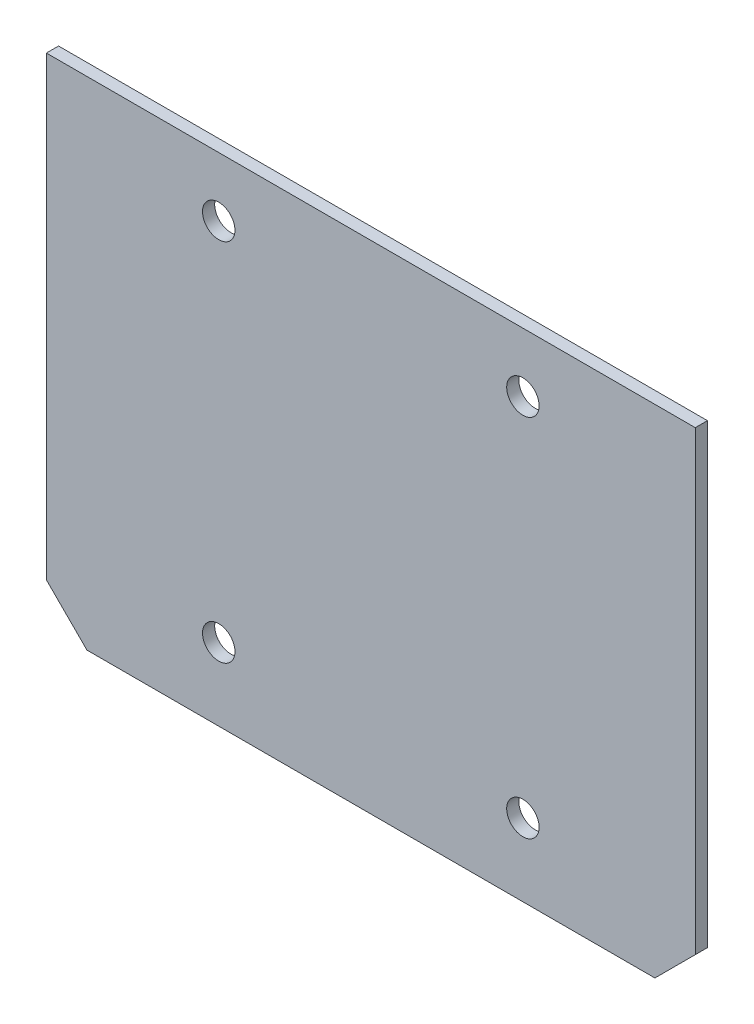
SolidWorks part; units mm, degrees
ref_plane "Front Plane" through (0, 0, 0) normal (0, 0, 1) x (1, 0, 0)
ref_plane "Top Plane" through (0, 0, 0) normal (0, 1, 0) x (1, 0, 0)
ref_plane "Right Plane" through (0, 0, 0) normal (1, 0, 0) x (0, 0, -1)
sketch "Sketch2" plane through (0, 0, 9.8018) normal (0, 0, 1) x (1, 0, 0)
  line L0 (-28, -37.4132) -> (-32, -33.4132)
  line L1 (-32, -33.4132) -> (-32, 11.5868)
  line L2 (-32, 11.5868) -> (32, 11.5868)
  line L3 (32, 11.5868) -> (32.0175, -33.4132)
  line L4 (32.0175, -33.4132) -> (28.0175, -37.4132)
  line L5 (28.0175, -37.4132) -> (-28, -37.4132)
  circle A0 centre (-15, 5.7446) radius 1.6
  circle A1 centre (15, 5.7446) radius 1.6
  circle A2 centre (-15, -30.2554) radius 1.6
  circle A3 centre (15, -30.2554) radius 1.6
extrude "Boss-Extrude1" add sketch "Sketch2" along normal blind 1.2
